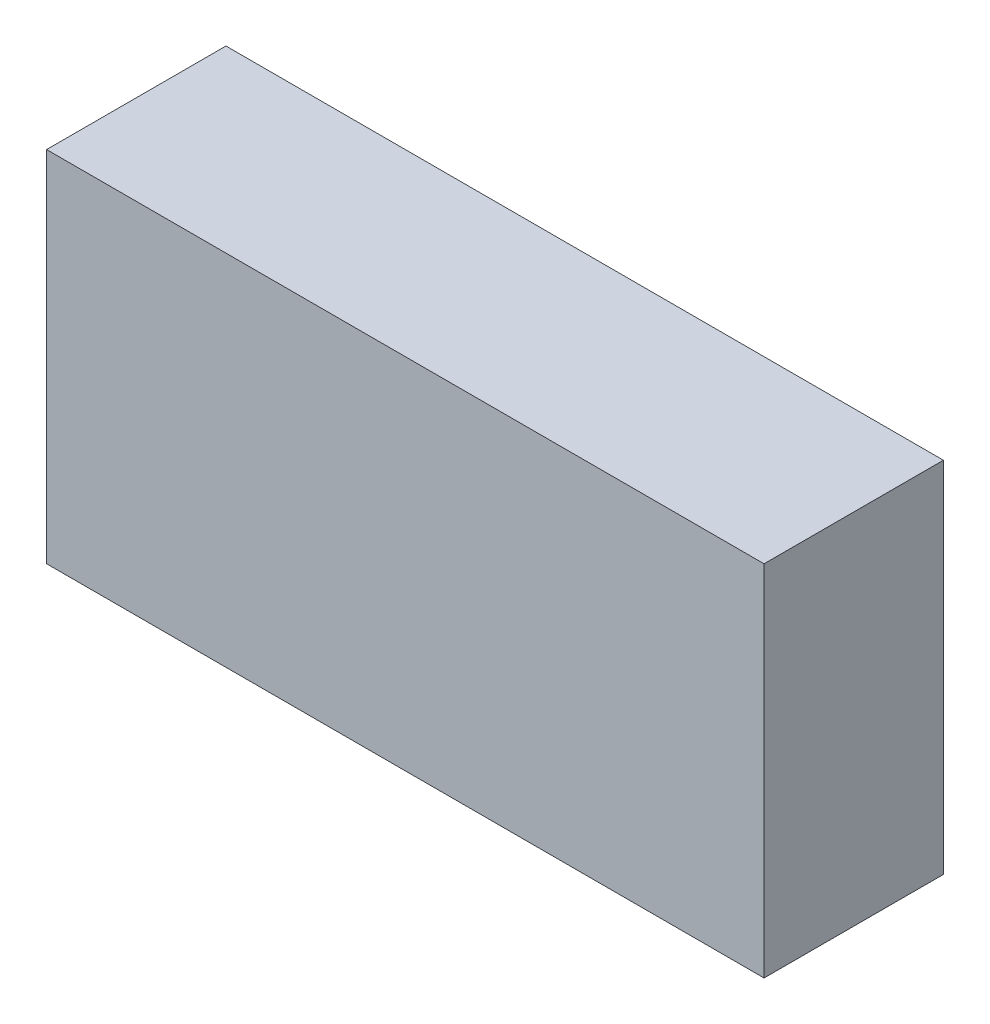
SolidWorks part; units mm, degrees
ref_plane "Front Plane" through (0, 0, 0) normal (0, 0, 1) x (1, 0, 0)
ref_plane "Top Plane" through (0, 0, 0) normal (0, 1, 0) x (1, 0, 0)
ref_plane "Right Plane" through (0, 0, 0) normal (1, 0, 0) x (0, 0, -1)
sketch "RectangleSketch" plane through (0, 0, 0) normal (0, 0, 1) x (1, 0, 0)
  line L1 (0, 0) -> (40, 0)
  line L2 (0, 0) -> (0, 20)
  line L3 (0, 20) -> (40, 20)
  line L4 (40, 0) -> (40, 20)
  dimension "width_mm" = 40
  dimension "height_mm" = 20
extrude "BlindBoss" add sketch "RectangleSketch" along normal blind 10 separate body
